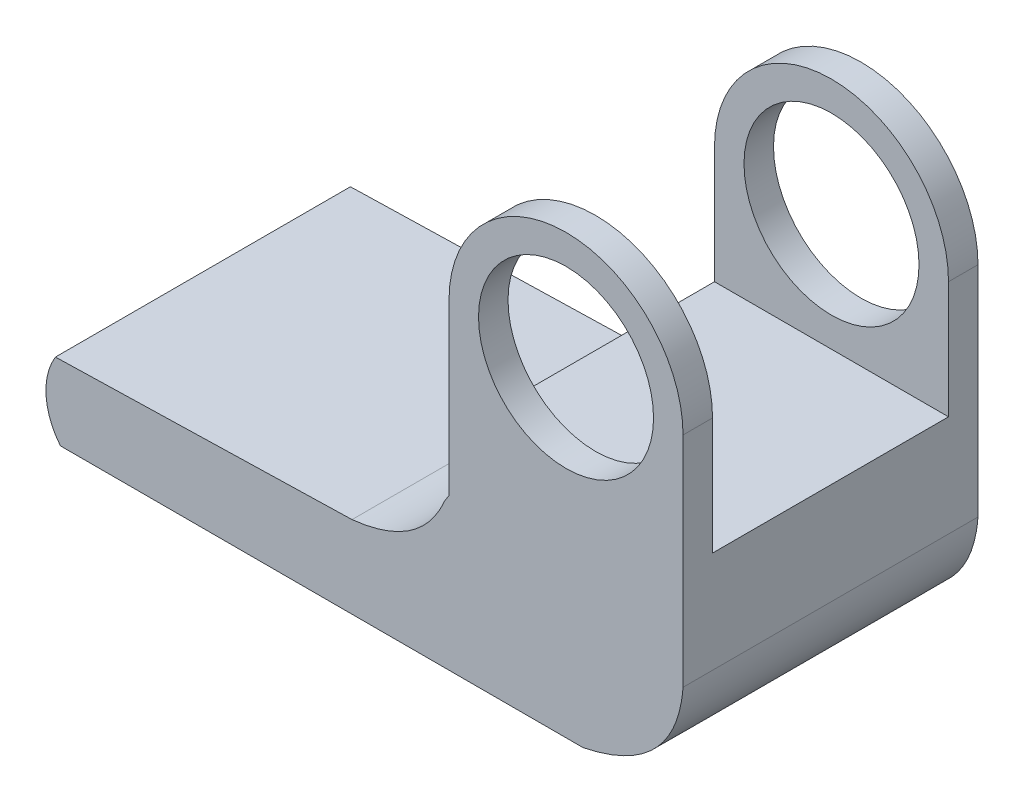
SolidWorks part; units mm, degrees
ref_plane "Front Plane" through (0, 0, 0) normal (0, 0, 1) x (1, 0, 0)
ref_plane "Top Plane" through (0, 0, 0) normal (0, 1, 0) x (1, 0, 0)
ref_plane "Right Plane" through (0, 0, 0) normal (1, 0, 0) x (0, 0, -1)
sketch "Sketch1" plane through (0, 0, 0) normal (0, 0, 1) x (1, 0, 0)
  line L0 (-11.9, 0) -> (-11.9, -17.2546)
  line L1 (-11.9, -17.2546) -> (-12.3014, -17.8366)
  line L4 (-51.4207, -32.6222) -> (1.7322, -32.6222)
  line L6 (11.9, -22.2213) -> (11.9, 0)
  line L7 (-21.7646, -24.2845) -> (-51.9306, -25.0496)
  circle A0 centre (0, 0) radius 8.9
  arc A1 (11.9, 0) -> (-11.9, 0) centre (0, 0) ccw
  arc A2 (-51.9306, -25.0496) -> (-51.4207, -32.6222) centre (-46.3598, -28.478) ccw
  spline S0 degree 2 poles (1.7322, -32.6222) (11.2482, -30.6652) (11.9, -22.2213) knots 0 0 0 1 1 1
  spline S1 degree 2 poles (-21.7646, -24.2845) (-14.0586, -23.4565) (-11.9, -16.7527) knots 0 0 0 1 1 1
  point P6 (-12.3934, -19.9564)
  point P13 (-14.0026, -20.6325)
  point P19 (-47.5748, -29.6249)
  point P20 (-51.4207, -32.6222)
  point P21 (-21.7087, -24.2912)
  dimension "D1" = 17.8
  dimension "D2" = 23.8
  dimension "D3" = 53.1529
  dimension "D4" = 30.1757
extrude "Boss-Extrude1" add sketch "Sketch1" along normal blind 30 contours S1 L7 A2 L4 S0 L6 A1 L0 L1 A0
sketch "Sketch2" plane through (-11.9, 0, 0) normal (-1, 0, 0) x (0, 0, 1)
  line L0 (0, 0) -> (0, -17.2546) construction
  line L1 (3, -11.9) -> (27, -11.9)
  line L2 (3, -11.9) -> (3, 11.9)
  line L3 (3, 11.9) -> (27, 11.9)
  line L4 (27, -11.9) -> (27, 11.9)
  line L5 (30, 0) -> (30, -17.2546) construction
  line L6 (30, 11.9) -> (0, 11.9) construction
  dimension "D1" = 3
  dimension "D2" = 3
  dimension "D3" = 23.8
extrude "Cut-Extrude1" cut sketch "Sketch2" against normal up to surface (23.8 mm away) up to face at (11.9, -11.1106, 15)
